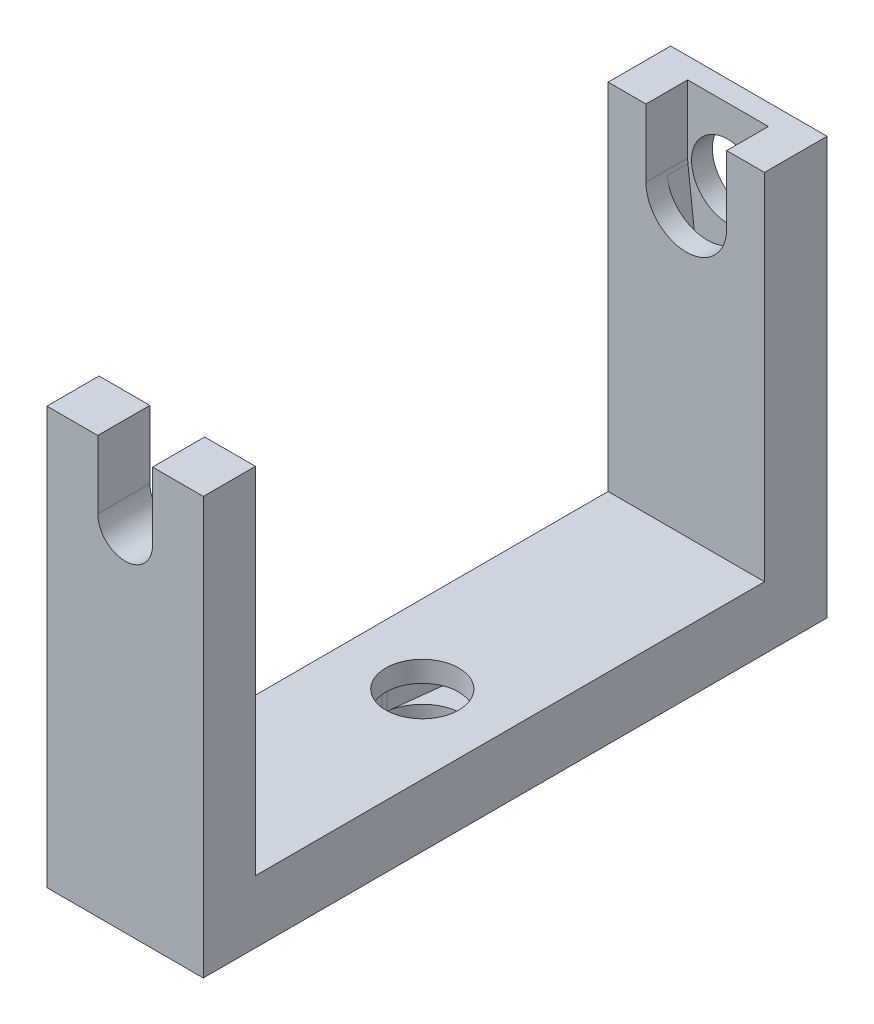
SolidWorks part; units mm, degrees
ref_plane "Front Plane" through (0, 0, 0) normal (0, 0, 1) x (1, 0, 0)
ref_plane "Top Plane" through (0, 0, 0) normal (0, 1, 0) x (1, 0, 0)
ref_plane "Right Plane" through (0, 0, 0) normal (1, 0, 0) x (0, 0, -1)
sketch "Sketch1" plane through (0, 0, 0) normal (1, 0, 0) x (0, 0, -1)
  line L0 (-15.91, -3) -> (-15.91, 3)
  line L1 (-15.91, 3) -> (15.91, 3)
  line L2 (15.91, 3) -> (15.91, 37)
  line L3 (15.91, 37) -> (21.91, 37)
  line L4 (21.91, 37) -> (21.91, -3)
  line L5 (21.91, -3) -> (-15.91, -3)
  line L6 (-15.91, 0) -> (0, 0) construction
  line L7 (0, 0) -> (0, 3) construction
  dimension "D1" = 31.82
  dimension "D2" = 6
  dimension "D3" = 40
  dimension "D4" = 6
extrude "Boss-Extrude1" add sketch "Sketch1" along normal mid plane 15
sketch "Sketch2" plane through (0, 0, 0) normal (0, 1, 0) x (1, 0, 0)
  line L0 (0, -12.91) -> (0, -15.91) construction
  line L1 (7.5, -15.91) -> (-7.5, -15.91) construction
  circle A0 centre (0, -9.41) radius 3.5
  dimension "D1" = 7
  dimension "D2" = 3
extrude "Cut-Extrude1" cut sketch "Sketch2" along normal through all
sketch "Sketch3" plane through (0, 0, 0) normal (0, 1, 0) x (1, 0, 0)
  circle A2 centre (0, -9.41) radius 3.5 construction
  line B0 (3.596, -8.9935) -> (1.9867, 4.9001)
  line B1 (-1.9867, 4.9001) -> (-3.596, -8.9935)
  arc B2 (-3.596, -8.9935) -> (3.596, -8.9935) centre (0, -9.41) ccw
  arc B3 (1.9867, 4.9001) -> (-1.9867, 4.9001) centre (0, 4.67) ccw
  line B4 (0, 4.67) -> (0, -9.41)
sketch_block_instance "Block1-1"
sketch_block "Block1" parameters "D1"=14.1918
ref_plane "Plane1" through (0, 0, -18.91) normal (0, 0, 1) x (1, 0, 0)
sketch "Sketch6" plane through (0, 0, -18.91) normal (0, 0, 1) x (1, 0, 0)
  line L0 (0, 34) -> (0, 37) construction
  line L2 (7.5, 37) -> (-7.5, 37) construction
  circle A0 centre (0, 30.5) radius 3.5
  dimension "D2" = 7
  dimension "D1" = 3
extrude "Cut-Extrude4" cut sketch "Sketch6" against normal through all
sketch "Sketch7" plane through (0, 0, -18.91) normal (0, 0, 1) x (1, 0, 0)
  line L0 (2.2351, 16.1611) -> (3.8443, 30.0547)
  line L1 (-3.8443, 30.0547) -> (-2.2351, 16.1611)
  line L2 (1.9867, 16.1899) -> (3.596, 30.0835)
  line L3 (-3.596, 30.0835) -> (-1.9867, 16.1899)
  line L4 (1.9867, 16.1899) -> (3.596, 30.0835) construction
  line L5 (-3.596, 30.0835) -> (-1.9867, 16.1899) construction
  line L6 (3.87, 30.5) -> (3.87, 37)
  line L7 (3.87, 37) -> (-3.87, 37)
  line L8 (-3.87, 37) -> (-3.87, 30.5)
  line L9 (7.5, 37) -> (-7.5, 37) construction
  arc A0 (3.8443, 30.0547) -> (3.87, 30.5) centre (0, 30.5) ccw
  arc A1 (-2.2351, 16.1611) -> (2.2351, 16.1611) centre (0, 16.42) ccw
  arc A2 (-1.9867, 16.1899) -> (1.9867, 16.1899) centre (0, 16.42) ccw
  arc A3 (3.596, 30.0835) -> (-3.596, 30.0835) centre (0, 30.5) ccw
  arc A4 (-1.9867, 16.1899) -> (1.9867, 16.1899) centre (0, 16.42) ccw construction
  arc A5 (3.596, 30.0835) -> (-3.596, 30.0835) centre (0, 30.5) ccw construction
  arc A6 (-3.87, 30.5) -> (-3.8443, 30.0547) centre (0, 30.5) ccw
  arc A7 (3.8443, 30.0547) -> (-3.8443, 30.0547) centre (0, 30.5) ccw construction
  dimension "D1" = 0
  dimension "D2" = 0.25
extrude "Cut-Extrude5" cut sketch "Sketch7" against normal mid plane 2
sketch "Sketch8" plane through (0, 0, -19.91) normal (0, 0, 1) x (1, 0, 0)
  line L0 (3.87, 30.5) -> (3.87, 37) construction
  line L1 (-3.87, 37) -> (-3.87, 30.5) construction
  line L2 (3.87, 30.5) -> (3.87, 37)
  line L3 (-3.87, 37) -> (-3.87, 30.5)
  line L4 (-3.87, 37) -> (3.87, 37)
  arc A0 (3.87, 30.5) -> (-3.87, 30.5) centre (0, 30.5) cw
extrude "Cut-Extrude6" cut sketch "Sketch8" along normal through all
sketch "Sketch9" plane through (0, 0, 0) normal (0, 1, 0) x (1, 0, 0)
  line L5 (-3.87, -9.41) -> (-3.87, -15.91)
  line L6 (7.5, -15.91) -> (-7.5, -15.91) construction
  line L7 (3.8443, -8.9647) -> (2.2351, 4.9289)
  line L8 (-2.2351, 4.9289) -> (-3.8443, -8.9647)
  line L9 (3.8443, -8.9647) -> (2.2351, 4.9289)
  line L10 (-2.2351, 4.9289) -> (-3.8443, -8.9647)
  line L11 (-3.87, -15.91) -> (3.87, -15.91)
  line L12 (3.87, -15.91) -> (3.87, -9.41)
  arc A6 (3.87, -9.41) -> (3.8443, -8.9647) centre (0, -9.41) ccw
  arc A8 (-3.8443, -8.9647) -> (3.8443, -8.9647) centre (0, -9.41) ccw
  arc A9 (2.2351, 4.9289) -> (-2.2351, 4.9289) centre (0, 4.67) ccw
  arc A10 (-3.8443, -8.9647) -> (-3.87, -9.41) centre (0, -9.41) ccw
  arc A11 (2.2351, 4.9289) -> (-2.2351, 4.9289) centre (0, 4.67) ccw
  dimension "D1" = 0.25
extrude "Cut-Extrude7" cut sketch "Sketch9" against normal mid plane 2
sketch "Sketch10" plane through (0, 0, 0) normal (0, 1, 0) x (1, 0, 0)
  line L0 (-3.87, -15.91) -> (3.87, -15.91) construction
  line L1 (-3.87, -9.41) -> (-3.87, -15.91) construction
  line L2 (3.87, -15.91) -> (3.87, -9.41) construction
  line L3 (-3.87, -15.91) -> (3.87, -15.91)
  line L4 (-3.87, -9.41) -> (-3.87, -15.91)
  line L5 (3.87, -15.91) -> (3.87, -9.41)
  arc A0 (-3.87, -9.41) -> (3.87, -9.41) centre (0, -9.41) cw
extrude "Cut-Extrude8" cut sketch "Sketch10" against normal through all
sketch "Sketch11" plane through (0, 0, 15.91) normal (0, 0, 1) x (1, 0, 0)
  line L8 (-7.5, -3) -> (-3.87, -3)
  line L9 (-3.87, -3) -> (-3.87, 1)
  line L10 (-3.87, 1) -> (3.87, 1)
  line L11 (3.87, 1) -> (3.87, -3)
  line L12 (3.87, -3) -> (7.5, -3)
  line L13 (7.5, -3) -> (7.5, 3)
  line L14 (7.5, 3) -> (-7.5, 3)
  line L15 (-7.5, 3) -> (-7.5, -3)
  line L16 (-7.5, -3) -> (-3.87, -3)
  line L17 (-3.87, -3) -> (-3.87, 1)
  line L18 (-3.87, 1) -> (3.87, 1)
  line L19 (3.87, 1) -> (3.87, -3)
  line L20 (3.87, -3) -> (7.5, -3)
  line L21 (7.5, -3) -> (7.5, 3)
  line L22 (7.5, 3) -> (-7.5, 3)
  line L23 (-7.5, 3) -> (-7.5, -3)
  dimension "D1" = 0
extrude "Boss-Extrude2" add sketch "Sketch11" along normal blind 22
sketch "Sketch12" plane through (0, -3, 0) normal (0, -1, 0) x (1, 0, 0)
  line L0 (7.5, 37.91) -> (7.5, -21.91) construction
  line L1 (-7.5, 37.91) -> (7.5, 37.91)
  line L2 (-7.5, 37.91) -> (-7.5, 32.91)
  line L3 (-7.5, 32.91) -> (7.5, 32.91)
  line L4 (7.5, 37.91) -> (7.5, 32.91)
  dimension "D1" = 5
extrude "Boss-Extrude3" add sketch "Sketch12" against normal up to surface (40 mm away)
sketch "Sketch13" plane through (0, 1, 0) normal (0, -1, 0) x (1, 0, 0)
  line L0 (3.87, 32.91) -> (-3.87, 32.91) construction
  line L1 (-3.87, 32.91) -> (3.87, 32.91) construction
  point P0 (0, 32.91)
  point P3 (0, 0)
  point P4 (0, 14.4121)
  point P5 (0, 0)
  line B0 (-3.596, 28.8735) -> (-1.9867, 14.9799)
  line B1 (0, 15.21) -> (0, 29.29)
sketch_block_instance "Block1-2"
sketch "Sketch14" plane through (0, 0, 37.91) normal (0, 0, 1) x (1, 0, 0)
  line L0 (-2.625, 37) -> (-2.625, 30.5)
  line L1 (-7.5, 37) -> (7.5, 37) construction
  line L2 (2.625, 30.5) -> (2.625, 37)
  line L3 (2.625, 37) -> (-2.625, 37)
  arc A0 (-2.625, 30.5) -> (2.625, 30.5) centre (0, 30.5) ccw
  circle A1 centre (0, 30.5) radius 3.5 construction
  dimension "D1" = 5.25
extrude "Cut-Extrude9" cut sketch "Sketch14" against normal up to surface (5 mm away) up to face at (0, 20, 32.91)
